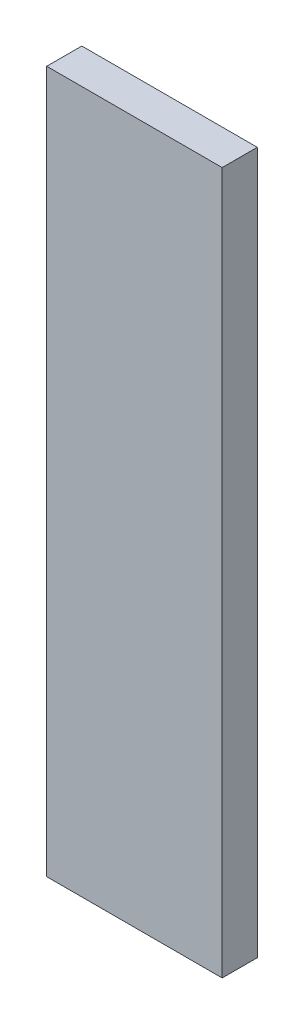
SolidWorks part; units mm, degrees
ref_plane "Front Plane" through (0, 0, 0) normal (0, 0, 1) x (1, 0, 0)
ref_plane "Top Plane" through (0, 0, 0) normal (0, 1, 0) x (1, 0, 0)
ref_plane "Right Plane" through (0, 0, 0) normal (1, 0, 0) x (0, 0, -1)
sketch "Sketch1" plane through (0, 0, 0) normal (0, 0, 1) x (1, 0, 0)
  line L1 (-15, 60) -> (15, 60)
  line L2 (-15, 60) -> (-15, -60)
  line L3 (-15, -60) -> (15, -60)
  line L4 (15, 60) -> (15, -60)
  line L5 (-15, 60) -> (15, -60) construction
  line L6 (-15, -60) -> (15, 60) construction
  point P0 (0, 0)
  dimension "D1" = 30
  dimension "D2" = 120
extrude "Boss-Extrude1" add sketch "Sketch1" along normal blind 6
